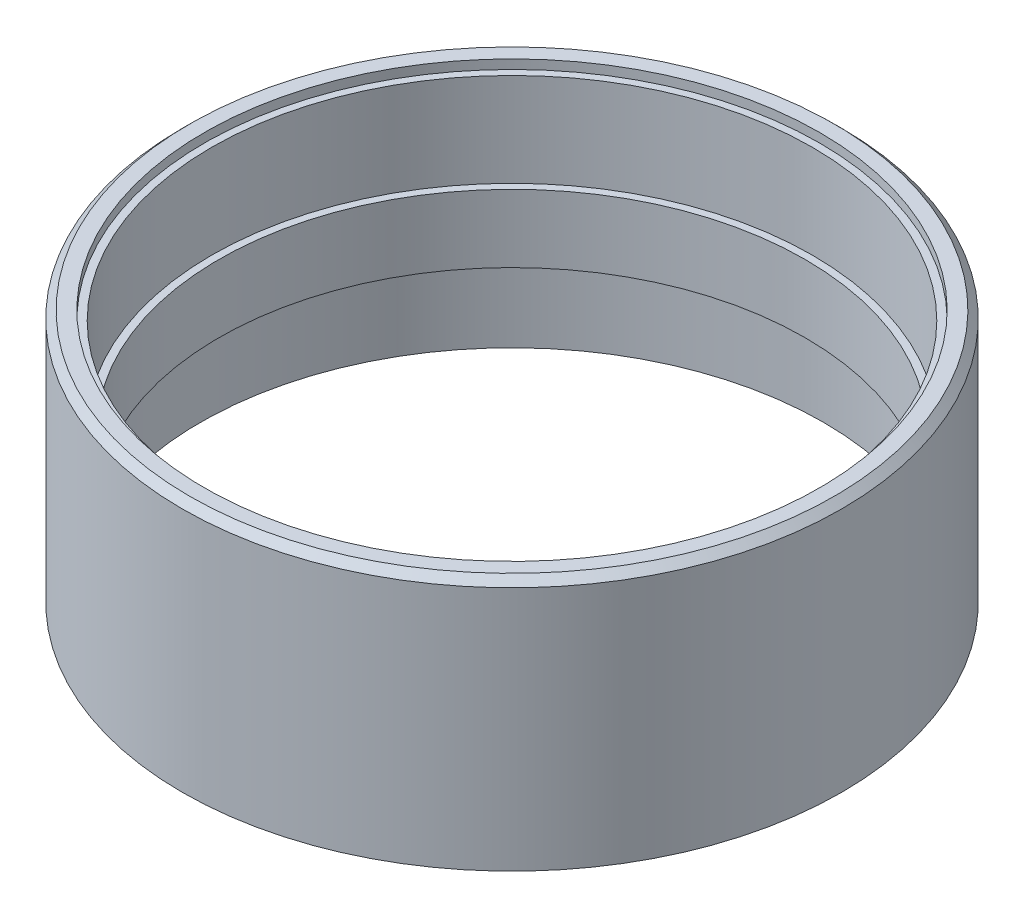
SolidWorks part; units mm, degrees
material "6061 Alloy"
ref_plane "Front Plane" through (0, 0, 0) normal (0, 0, 1) x (1, 0, 0)
ref_plane "Top Plane" through (0, 0, 0) normal (0, 1, 0) x (1, 0, 0)
ref_plane "Right Plane" through (0, 0, 0) normal (1, 0, 0) x (0, 0, -1)
sketch "Sketch1" plane through (0, 0, 0) normal (0, 0, 1) x (1, 0, 0)
  line L0 (21.336, 16.891) -> (21.336, 17.526)
  line L1 (22.86, 17.526) -> (22.86, 0)
  line L2 (20.32, 8.89) -> (22.86, 8.89) construction
  line L3 (0, -7.7413) -> (0, 33.0894) construction
  line L8 (22.86, 17.526) -> (21.336, 17.526)
  line L15 (21.59, 5.588) -> (21.59, 2.413)
  line L16 (22.225, 0) -> (22.86, 0)
  line L17 (22.225, 2.413) -> (22.225, 0)
  line L18 (21.59, 2.413) -> (22.225, 2.413)
  line L19 (20.828, 16.256) -> (20.828, 10.414)
  line L20 (21.59, 5.715) -> (21.59, 5.588)
  line L21 (20.32, 5.715) -> (21.59, 5.715)
  line L22 (20.32, 10.414) -> (20.32, 5.715)
  line L23 (20.828, 10.414) -> (20.32, 10.414)
  line L24 (20.828, 16.891) -> (20.828, 16.256)
  line L25 (21.336, 16.891) -> (20.828, 16.891)
  dimension "D1" = 0.635
  dimension "D2" = 0.508
  dimension "D3" = 0.635
  dimension "D4" = 5.842
  dimension "D5" = 4.699
  dimension "D6" = 0.127
  dimension "D7" = 3.175
  dimension "D8" = 2.413
  dimension "D9" = 0.635
  dimension "D10" = 0.635
  dimension "D11" = 1.27
  dimension "D12" = 0.508
  dimension "D13" = 20.32
  dimension "D14" = 17.526
  dimension "D15" = 22.86
  dimension "D16" = 20.828
  dimension "D17" = 21.336
  dimension "D18" = 1.524
  dimension "D19" = 8.636
revolve "Revolve1" add sketch "Sketch1" angle 360 about L3
chamfer "Chamfer1" distance 0.508 angle 45 1 edges at (0, 17.526, -22.86)
chamfer "Chamfer2" distance 0.254 angle 45 1 edges at (0, 0, -22.225)
sketch "Sketch2" plane through (0, 0, 0) normal (0, -1, 0) x (1, 0, 0)
  circle A0 centre (0, 0) radius 22.86
  circle A1 centre (0, 0) radius 21.59
extrude "Boss-Extrude1" add sketch "Sketch2" against normal up to next
